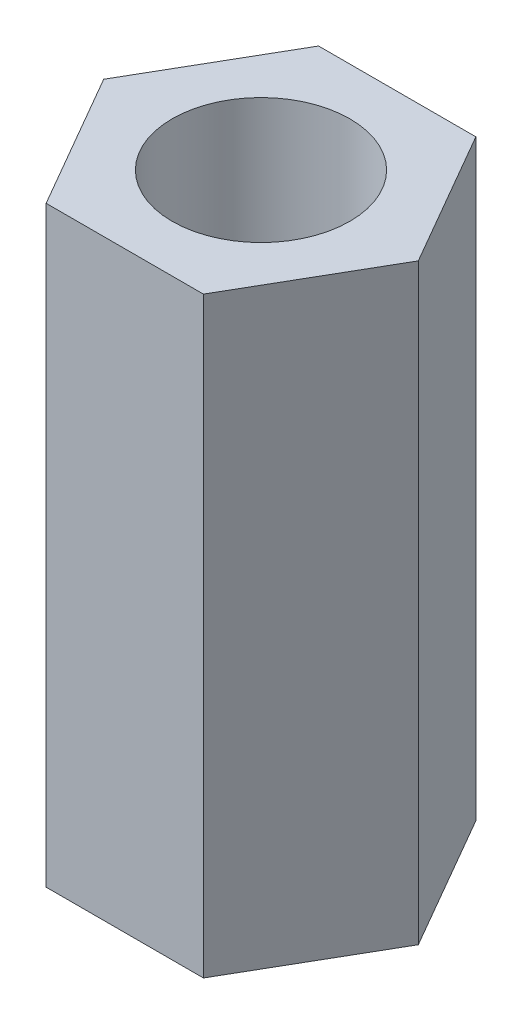
SolidWorks part; units mm, degrees
ref_plane "Front Plane" through (0, 0, 0) normal (0, 0, 1) x (1, 0, 0)
ref_plane "Top Plane" through (0, 0, 0) normal (0, 1, 0) x (1, 0, 0)
ref_plane "Right Plane" through (0, 0, 0) normal (1, 0, 0) x (0, 0, -1)
sketch "Sketch1" plane through (0, 0, 0) normal (0, 1, 0) x (1, 0, 0)
  line L1 (1.3279, -2.3) -> (2.6558, 0)
  line L2 (2.6558, 0) -> (1.3279, 2.3)
  line L3 (1.3279, 2.3) -> (-1.3279, 2.3)
  line L4 (-1.3279, 2.3) -> (-2.6558, 0)
  line L5 (-2.6558, 0) -> (-1.3279, -2.3)
  line L6 (-1.3279, -2.3) -> (1.3279, -2.3)
  circle A0 centre (0, 0) radius 2.3 construction
  circle A1 centre (0, 0) radius 1.5
  dimension "D1" = 3
  dimension "D2" = 4.6
extrude "Boss-Extrude1" add sketch "Sketch1" along normal blind 10
